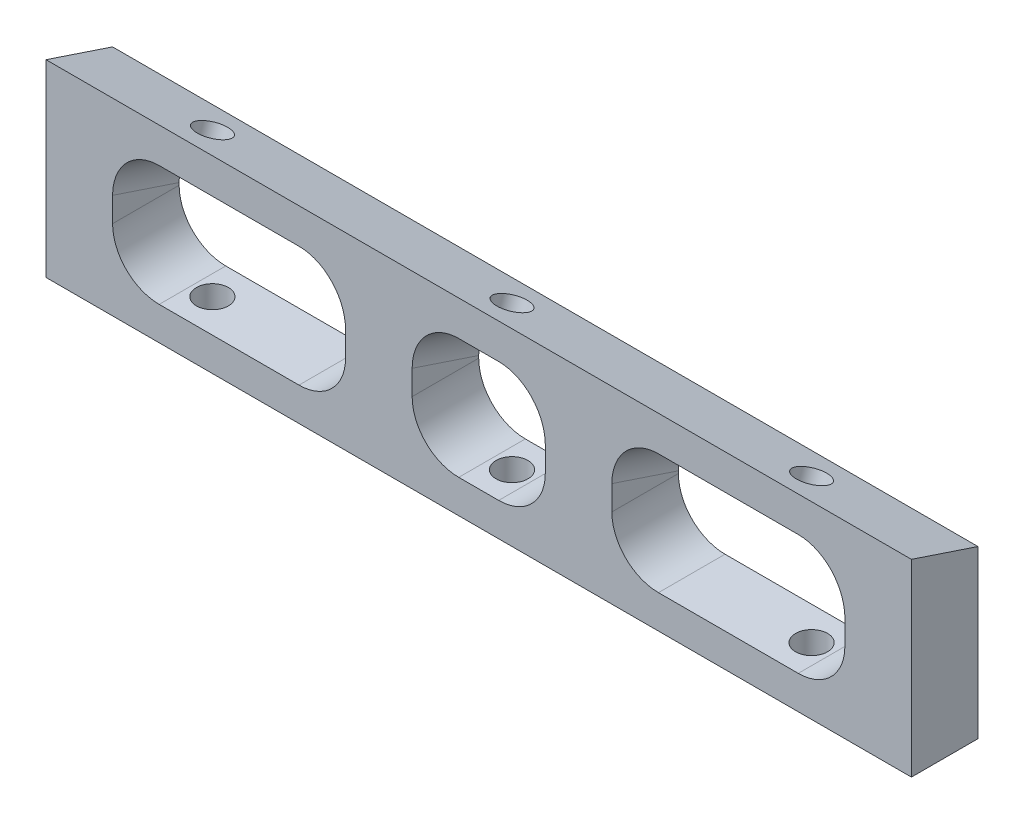
SolidWorks part; units mm, degrees
ref_plane "Plan de face" through (0, 0, 0) normal (0, 0, 1) x (1, 0, 0)
ref_plane "Plan de dessus" through (0, 0, 0) normal (0, 1, 0) x (1, 0, 0)
ref_plane "Plan de droite" through (0, 0, 0) normal (1, 0, 0) x (0, 0, -1)
sketch "Esquisse1" plane through (0, 0, 0) normal (1, 0, 0) x (0, 0, -1)
  line L0 (0, 0) -> (10, 0)
  line L1 (10, 0) -> (0, 3.3324)
  line L2 (0, 3.3324) -> (0, 0)
  line L3 (0, 0) -> (0, -1.9379)
  line L4 (10, -5.2703) -> (10, 0)
  line L5 (0, -1.9379) -> (10, -5.2703)
  line L6 (0, 0) -> (10, 0)
  line L7 (0, 0) -> (0, -25)
  line L8 (10, 0) -> (10, -25)
  line L9 (0, -25) -> (10, -25)
  line L10 (0, -25) -> (10, -25)
  line L11 (0, -25) -> (0, -20)
  line L12 (10, -25) -> (10, -20)
  line L13 (0, -20) -> (10, -20)
  dimension "D1" = 10
  dimension "D2" = 18.43
  dimension "D3" = 5
  dimension "D4" = 25
  dimension "D5" = 5
extrude "Boss.-Extru.1" add sketch "Esquisse1" along normal blind 110 contours L1 L2 L0 | L3 L5 L4 L0 | L13 L7 L9 L8
sketch "Esquisse2" plane through (0, 0, 0) normal (-1, 0, 0) x (0, 0, 1)
  line L0 (-10, 0) -> (0, 0)
  line L1 (-10, 0) -> (-10, -25)
  line L2 (0, 0) -> (0, -25)
  line L3 (-10, -25) -> (0, -25)
  line L4 (-10, 0) -> (0, 3.3324)
  line L5 (0, 3.3324) -> (0, 0)
  line L6 (0, -25) -> (-10, -25) construction
  line M5 (0, 3.3324) -> (-10, 0)
  line M6 (-10, 0) -> (-10, -5.2703)
  line M7 (-10, -5.2703) -> (0, -1.9379)
  line M8 (0, -1.9379) -> (0, 3.3324)
extrude "Boss.-Extru.2" add sketch "Esquisse2" along normal blind 10 contours L0 M5 M8 | L0 M6 M7 M8 | L1 L3 L2 M7
sketch "Esquisse3" plane through (110, 0, 0) normal (1, 0, 0) x (0, 0, -1)
  line L0 (10, 0) -> (0, 0)
  line L1 (10, 0) -> (10, -25)
  line L2 (0, 0) -> (0, -25)
  line L3 (10, -25) -> (0, -25)
  line L4 (0, 3.3324) -> (0, 0)
  line L5 (10, 0) -> (0, 3.3324)
  line M1 (10, 0) -> (0, 3.3324)
  line M2 (0, 3.3324) -> (0, -1.9379)
  line M3 (0, -1.9379) -> (10, -5.2703)
  line M4 (10, -5.2703) -> (10, 0)
extrude "Boss.-Extru.3" add sketch "Esquisse3" along normal blind 10 contours L0 M1 M2 | L0 M4 M2 M3 | L3 L1 L2 M3
sketch "Esquisse4" plane through (0, 0, -10) normal (0, 0, -1) x (-1, 0, 0)
  line L0 (-85, 0) -> (-85, -25) construction
  line L1 (-120, 0) -> (10, 0) construction
  line L2 (10, -25) -> (-120, -25) construction
  line L3 (-85, -25) -> (-55, 0) construction
  line L4 (-55, 0) -> (-55, -25) construction
  line L5 (-55, -25) -> (-25, 0) construction
  line L6 (-25, 0) -> (-25, -25) construction
  line L7 (-75, 0) -> (-65, 0)
  line L8 (-75, 0) -> (-75, -25)
  line L9 (-65, 0) -> (-65, -25)
  line L10 (-75, -25) -> (-65, -25)
  line L11 (-45, 0) -> (-35, 0)
  line L12 (-45, 0) -> (-45, -25)
  line L13 (-35, 0) -> (-35, -25)
  line L14 (-45, -25) -> (-35, -25)
  dimension "D1" = 30
  dimension "D2" = 30
  dimension "D3" = 10
  dimension "D4" = 10
  dimension "D5" = 10
  dimension "D6" = 10
extrude "Boss.-Extru.4" add sketch "Esquisse4" against normal blind 10
sketch "Esquisse5" plane through (0, 2.9993, -0.9995) normal (0, 0.9487, -0.3161) x (1, 0, 0)
  line L0 (-10, 4.2168) -> (120, 4.2168) construction
  line L1 (-10, -1.0535) -> (-10, 9.4871) construction
  line L2 (120, 9.4871) -> (120, -1.0535) construction
  circle A0 centre (10, 4.2168) radius 2.4
  circle A1 centre (55, 4.2168) radius 2.4
  circle A2 centre (100, 4.2168) radius 2.4
  dimension "D1" = 4.8
  dimension "D2" = 4.8
  dimension "D3" = 4.8
  dimension "D4" = 20
  dimension "D5" = 20
extrude "Enlèv. mat.-Extru.1" cut sketch "Esquisse5" against normal blind 10
sketch "Esquisse6" plane through (0, -25, 0) normal (0, -1, 0) x (1, 0, 0)
  line L0 (-10, -5) -> (120, -5) construction
  line L1 (-10, -10) -> (-10, 0) construction
  line L2 (120, -10) -> (120, 0) construction
  circle A0 centre (10, -5) radius 2.4
  circle A1 centre (55, -5) radius 2.4
  circle A2 centre (100, -5) radius 2.4
  dimension "D2" = 4.8
  dimension "D3" = 4.8
  dimension "D4" = 4.8
  dimension "D1" = 20
  dimension "D5" = 20
extrude "Enlèv. mat.-Extru.2" cut sketch "Esquisse6" against normal blind 10
fillet "Congé1" radius 7 12 edges at (45, -20, -5) (35, -20, -5) (65, -20, -5) (35, -3.6041, -5) (75, -20, -5) (110, -20, -5) (0, -20, -5) (0, -3.6041, -5) (75, -3.6041, -5) (110, -3.6041, -5) (65, -3.6041, -5) (45, -3.6041, -5)
